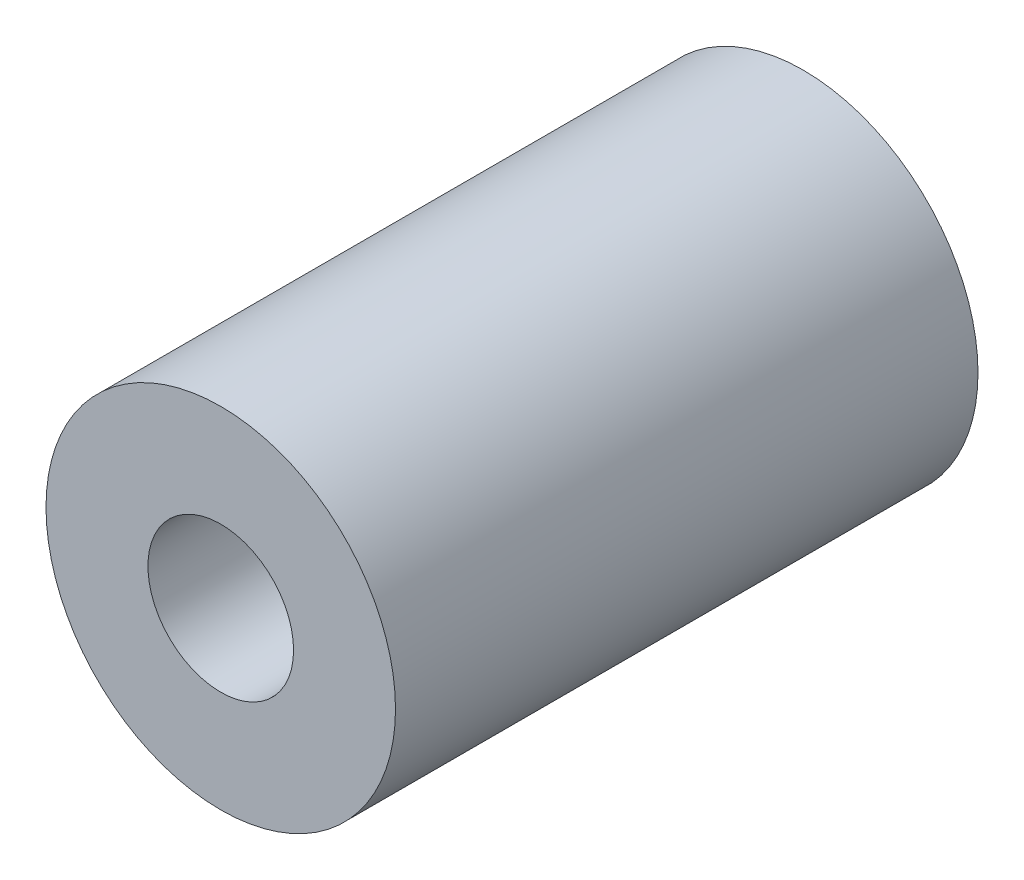
SolidWorks part; units mm, degrees
material "Aleación 1060"
ref_plane "Alzado" through (0, 0, 0) normal (0, 0, 1) x (1, 0, 0)
ref_plane "Planta" through (0, 0, 0) normal (0, 1, 0) x (1, 0, 0)
ref_plane "Vista lateral" through (0, 0, 0) normal (1, 0, 0) x (0, 0, -1)
sketch "Croquis1" plane through (0, 0, 0) normal (0, 0, 1) x (1, 0, 0)
  circle A0 centre (0, 0) radius 2.5
  circle A1 centre (0, 0) radius 6
  dimension "D1" = 5
  dimension "D2" = 12
extrude "Saliente-Extruir1" add sketch "Croquis1" along normal blind 20
sketch "Croquis3" plane through (0, 0, 0) normal (0, 1, 0) x (1, 0, 0)
  circle A0 centre (0, -4.1228) radius 0.8674
  circle A1 centre (0, -15.5897) radius 0.7272
extrude "Cortar-Extruir1" cut sketch "Croquis3" against normal through all
